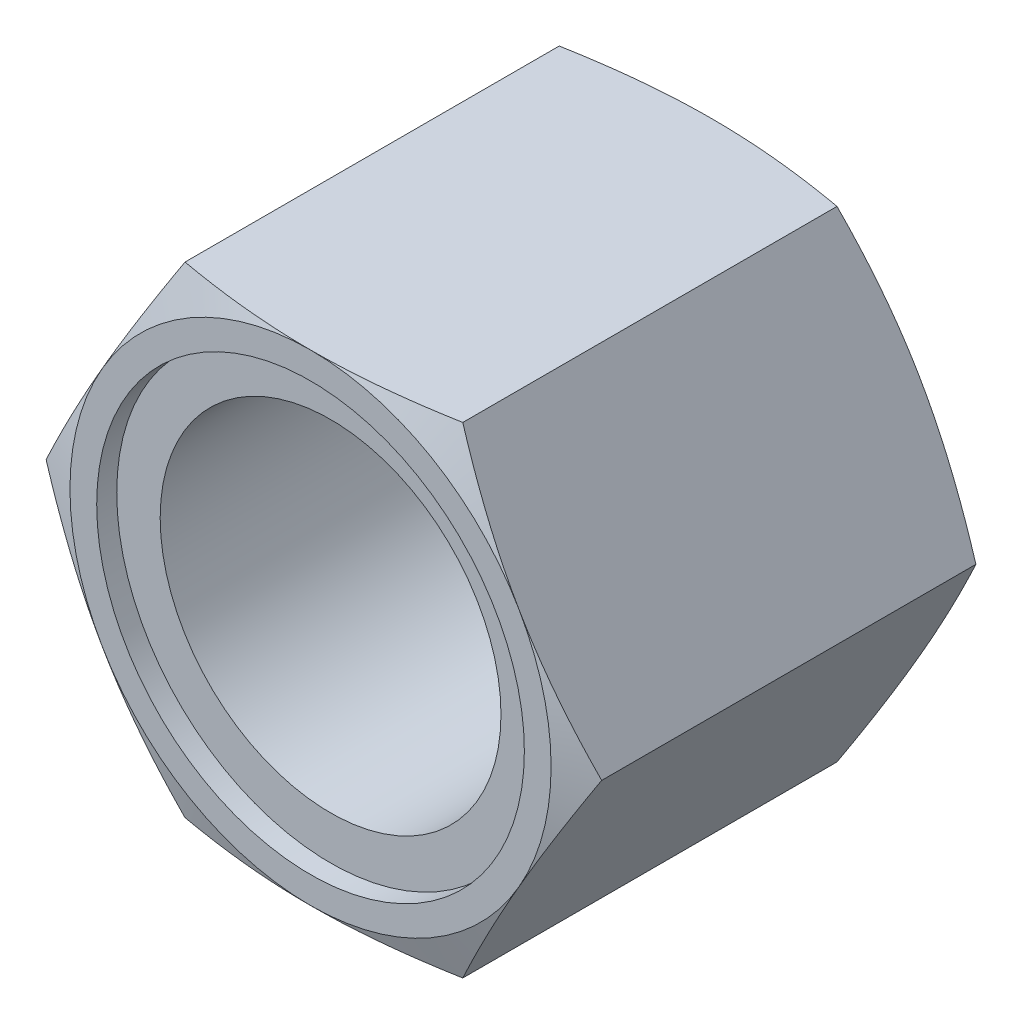
SolidWorks part; units mm, degrees
ref_plane "Плоскость1" through (0, 0, 0) normal (0, 0, 1) x (1, 0, 0)
ref_plane "Плоскость2" through (0, 0, 0) normal (0, 1, 0) x (1, 0, 0)
ref_plane "Плоскость3" through (0, 0, 0) normal (1, 0, 0) x (0, 0, -1)
sketch "Эскиз1" plane through (0, 0, 0) normal (0, 0, 1) x (1, 0, 0)
  line L1 (10.3923, 18) -> (-10.3923, 18)
  line L2 (-10.3923, 18) -> (-20.7846, 0)
  line L3 (-20.7846, 0) -> (-10.3923, -18)
  line L4 (-10.3923, -18) -> (10.3923, -18)
  line L5 (10.3923, -18) -> (20.7846, 0)
  line L6 (20.7846, 0) -> (10.3923, 18)
  circle A0 centre (0, 0) radius 18 construction
  dimension "D1" = 36
extrude "Вытянуть1" add sketch "Эскиз1" along normal blind 30
sketch "Эскиз2" plane through (0, 0, 30) normal (0, 0, 1) x (1, 0, 0)
  circle A0 centre (0, 0) radius 12.75
  dimension "D1" = 25.5
extrude "Вырез-Вытянуть1" cut sketch "Эскиз2" against normal blind 25
cosmetic thread "Условное изображение резьбы1" parameters "D2"=27
sketch "Эскиз3" plane through (0, 0, 5) normal (0, 0, 1) x (1, 0, 0)
  circle A0 centre (0, 0) radius 13.5
  dimension "D1" = 27
extrude "Вырез-Вытянуть2" cut sketch "Эскиз3" along normal blind 4
sketch "Эскиз4" plane through (0, 0, 30) normal (0, 0, 1) x (1, 0, 0)
  circle A0 centre (0, 0) radius 16
  dimension "D1" = 32
extrude "Вырез-Вытянуть3" cut sketch "Эскиз4" against normal blind 1.5
sketch "Эскиз5" plane through (0, 0, 0) normal (0, 1, 0) x (1, 0, 0)
  line L0 (20.7846, -30) -> (20.7846, -29)
  line L1 (20.7846, -30) -> (20.7846, 0) construction
  line L2 (20.7846, -29) -> (18, -30)
  line L3 (20.7846, -30) -> (10.3923, -30) construction
  line L4 (18, -30) -> (20.7846, -30)
  line L5 (20.7846, 0) -> (18, 0)
  line L6 (20.7846, 0) -> (10.3923, 0) construction
  line L7 (18, 0) -> (20.7846, -1)
  line L8 (20.7846, -1) -> (20.7846, 0)
  dimension "D1" = 1
  dimension "D2" = 2
ref_axis "Ось1" through (0, 0, 9) along (0, 0, 1)
revolve "Вырез-Повернуть1" cut sketch "Эскиз5" angle 360 about axis through (0, 0, 9) along (0, 0, 1)
